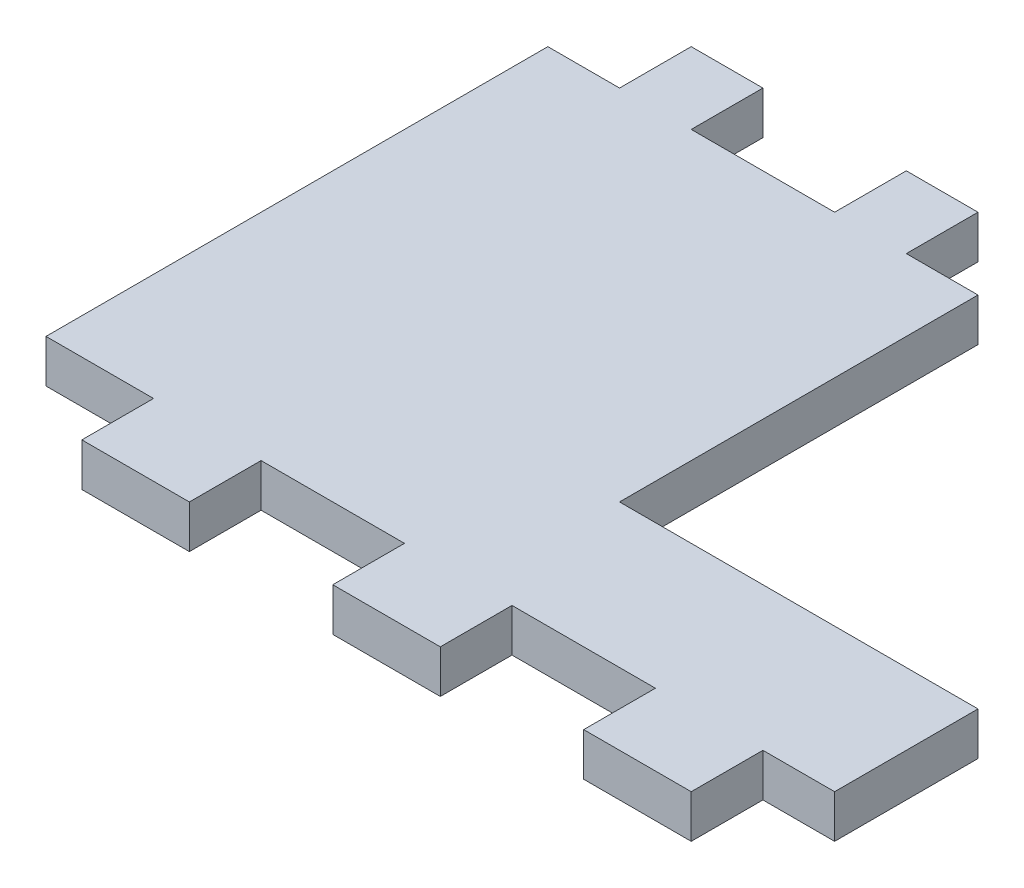
SolidWorks part; units mm, degrees
ref_plane "Front Plane" through (0, 0, 0) normal (0, 0, 1) x (1, 0, 0)
ref_plane "Top Plane" through (0, 0, 0) normal (0, 1, 0) x (1, 0, 0)
ref_plane "Right Plane" through (0, 0, 0) normal (1, 0, 0) x (0, 0, -1)
sketch "Sketch1" plane through (0, 0, 0) normal (0, 1, 0) x (1, 0, 0)
  line L0 (-40.9606, -36.8867) -> (-30.9606, -36.8867)
  line L1 (-73.4606, -36.8867) -> (-73.4606, -1.8867)
  line L2 (-18.4606, -36.8867) -> (-18.4606, -26.8867)
  line L3 (-43.4606, -1.8867) -> (-48.4606, -1.8867)
  line L4 (-18.4606, -26.8867) -> (-43.4606, -26.8867)
  line L5 (-30.9606, -36.8867) -> (-30.9606, -41.8867)
  line L6 (-40.9606, -41.8867) -> (-48.4606, -41.8867)
  line L7 (-68.4606, -1.8867) -> (-68.4606, 3.1133)
  line L8 (-48.4606, -36.8867) -> (-58.4606, -36.8867)
  line L9 (-58.4606, -41.8867) -> (-65.9606, -41.8867)
  line L10 (-65.9606, -41.8867) -> (-65.9606, -36.8867)
  line L11 (-65.9606, -36.8867) -> (-73.4606, -36.8867)
  line L12 (-43.4606, -26.8867) -> (-43.4606, -1.8867)
  line L13 (-30.9606, -41.8867) -> (-23.4606, -41.8867)
  line L14 (-23.4606, -41.8867) -> (-23.4606, -36.8867)
  line L15 (-58.4606, -41.8867) -> (-58.4606, -36.8867)
  line L16 (-23.4606, -36.8867) -> (-18.4606, -36.8867)
  line L17 (-68.4606, -1.8867) -> (-73.4606, -1.8867)
  line L18 (-48.4606, 3.1133) -> (-53.4606, 3.1133)
  line L19 (-48.4606, -41.8867) -> (-48.4606, -36.8867)
  line L20 (-68.4606, 3.1133) -> (-63.4606, 3.1133)
  line L21 (-63.4606, -1.8867) -> (-53.4606, -1.8867)
  line L22 (-63.4606, 3.1133) -> (-63.4606, -1.8867)
  line L23 (-40.9606, -41.8867) -> (-40.9606, -36.8867)
  line L25 (-53.4606, -1.8867) -> (-53.4606, 3.1133)
  line L26 (-48.4606, 3.1133) -> (-48.4606, -1.8867)
  point P1 (-30.9606, -39.3867)
  point P2 (-65.9606, -39.3867)
  dimension "D1" = 55
  dimension "D2" = 10
  dimension "D3" = 5
  dimension "D4" = 7.5
  dimension "D5" = 10
  dimension "D6" = 7.5
  dimension "D7" = 7.5
  dimension "D8" = 5
  dimension "D9" = 10
  dimension "D10" = 5
  dimension "D11" = 5
  dimension "D12" = 5
  dimension "D13" = 35
extrude "Boss-Extrude1" add sketch "Sketch1" along normal blind 3
